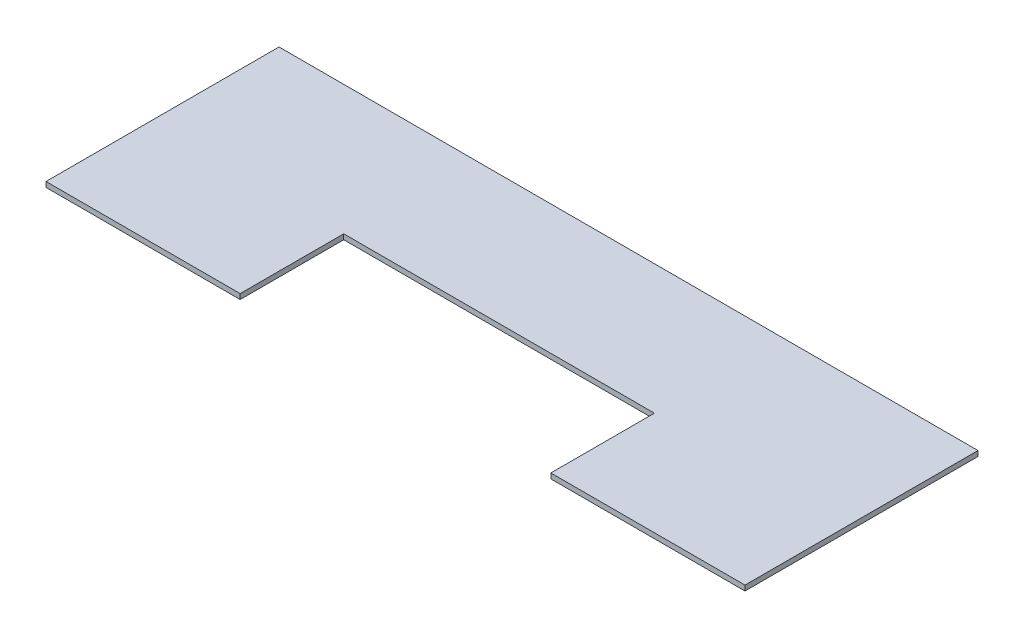
SolidWorks part; units mm, degrees
material "PVC"
ref_plane "前视基准面" through (0, 0, 0) normal (0, 0, 1) x (1, 0, 0)
ref_plane "上视基准面" through (0, 0, 0) normal (0, 1, 0) x (1, 0, 0)
ref_plane "右视基准面" through (0, 0, 0) normal (1, 0, 0) x (0, 0, -1)
sketch "草图1" plane through (0, 0, 0) normal (0, 1, 0) x (1, 0, 0)
  line L1 (-67.5, 22.5) -> (67.5, 22.5)
  line L2 (-67.5, 22.5) -> (-67.5, -22.5)
  line L3 (-67.5, -22.5) -> (67.5, -22.5)
  line L4 (67.5, 22.5) -> (67.5, -22.5)
  line L5 (0, -22.5) -> (0, 22.5) construction
  line L6 (-67.5, 0) -> (67.5, 0) construction
  line L7 (-30, -42.5) -> (30, -42.5)
  line L8 (-30, -42.5) -> (-30, -2.5)
  line L9 (-30, -2.5) -> (30, -2.5)
  line L10 (30, -42.5) -> (30, -2.5)
  line L11 (0, -2.5) -> (0, -42.5) construction
  line L12 (-30, -22.5) -> (30, -22.5) construction
  point P0 (0, 0)
  dimension "D1" = 135
  dimension "D2" = 45
  dimension "D3" = 60
  dimension "D4" = 40
extrude "凸台-拉伸1" add sketch "草图1" along normal blind 1 contours L10 L3 L4 L1 L2 L8 L9
